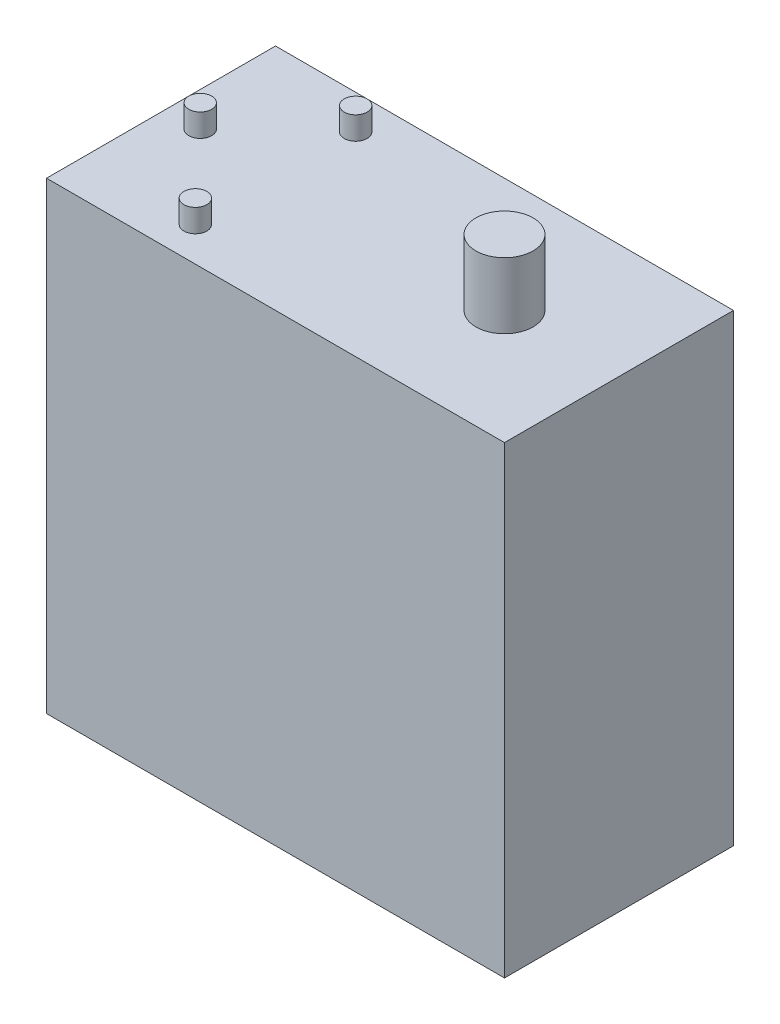
SolidWorks part; units mm, degrees
ref_plane "Front Plane" through (0, 0, 0) normal (0, 0, 1) x (1, 0, 0)
ref_plane "Top Plane" through (0, 0, 0) normal (0, 1, 0) x (1, 0, 0)
ref_plane "Right Plane" through (0, 0, 0) normal (1, 0, 0) x (0, 0, -1)
sketch "Sketch1" plane through (0, 0, 0) normal (0, 1, 0) x (1, 0, 0)
  line L1 (-16.2433, 10.7539) -> (23.7567, 10.7539)
  line L2 (-16.2433, 10.7539) -> (-16.2433, -9.2461)
  line L3 (-16.2433, -9.2461) -> (23.7567, -9.2461)
  line L4 (23.7567, 10.7539) -> (23.7567, -9.2461)
  dimension "D1" = 40
  dimension "D2" = 20
extrude "Boss-Extrude1" add sketch "Sketch1" along normal blind 40.5
sketch "Sketch2" plane through (0, 40.5, 0) normal (0, 1, 0) x (1, 0, 0)
  line L0 (23.7567, 10.7539) -> (-16.2433, 10.7539) construction
  line L1 (23.7567, -9.2461) -> (23.7567, 10.7539) construction
  circle A0 centre (13.7567, 0.7539) radius 2.5
  dimension "D1" = 10
  dimension "D2" = 10
extrude "Boss-Extrude2" add sketch "Sketch2" along normal blind 5.75 and the other way blind 46.25
sketch "Sketch3" plane through (0, 40.5, 0) normal (0, 1, 0) x (1, 0, 0)
  line L0 (-16.2433, 10.7539) -> (-16.2433, -9.2461) construction
  line L1 (-16.2433, -9.2461) -> (23.7567, -9.2461) construction
  circle A0 centre (-13.2433, 1.1808) radius 1
  circle A1 centre (-6.2433, 7.7539) radius 1
  circle A2 centre (-6.2433, -6.2461) radius 1
  dimension "D1" = 3
  dimension "D2" = 7
  dimension "D3" = 7
  dimension "D4" = 14
  dimension "D5" = 3
extrude "Boss-Extrude3" add sketch "Sketch3" along normal blind 2 and the other way blind 42.5
